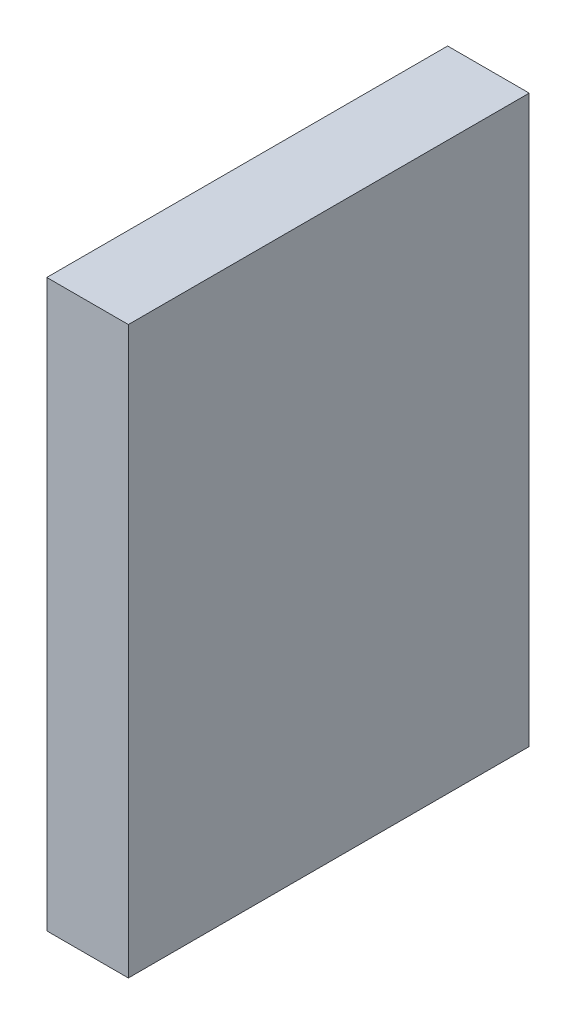
SolidWorks part; units mm, degrees
ref_plane "Front Plane" through (0, 0, 0) normal (0, 0, 1) x (1, 0, 0)
ref_plane "Top Plane" through (0, 0, 0) normal (0, 1, 0) x (1, 0, 0)
ref_plane "Right Plane" through (0, 0, 0) normal (1, 0, 0) x (0, 0, -1)
sketch "Sketch1" plane through (0, 0, 0) normal (1, 0, 0) x (0, 0, -1)
  line L1 (-101.1445, 186.055) -> (114.7555, 186.055)
  line L2 (-101.1445, 186.055) -> (-101.1445, -118.745)
  line L3 (-101.1445, -118.745) -> (114.7555, -118.745)
  line L4 (114.7555, 186.055) -> (114.7555, -118.745)
  dimension "D1" = 215.9
  dimension "D2" = 304.8
extrude "Boss-Extrude1" add sketch "Sketch1" along normal blind 43.942
